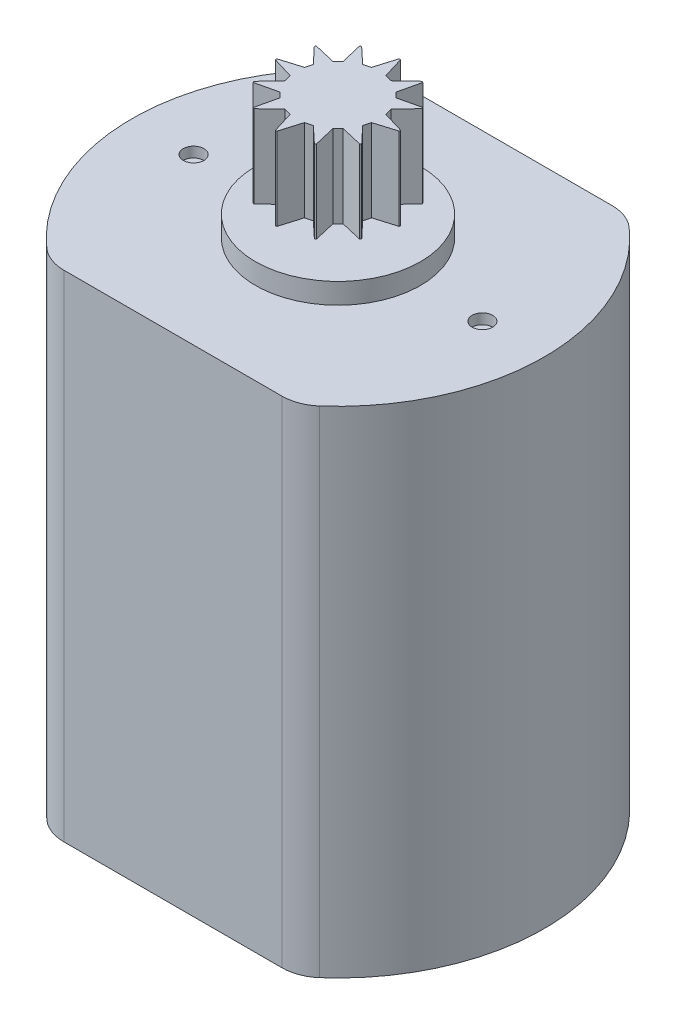
SolidWorks part; units mm, degrees
ref_plane "Front Plane" through (0, 0, 0) normal (0, 0, 1) x (1, 0, 0)
ref_plane "Top Plane" through (0, 0, 0) normal (0, 1, 0) x (1, 0, 0)
ref_plane "Right Plane" through (0, 0, 0) normal (1, 0, 0) x (0, 0, -1)
sketch "Sketch2" plane through (0, 0, 0) normal (0, 1, 0) x (1, 0, 0)
  line L0 (-6.4021, 0) -> (8.186, 0) construction
  line L1 (0, 6.5571) -> (0, -7.7951) construction
  line L2 (-5, 6.9212) -> (-5, -10.6509) construction
  line L3 (-3, 6.9212) -> (-3, -10.7038) construction
  line L4 (3, 7.4505) -> (3, -7.7928) construction
  line L5 (5, 7.4505) -> (5, -8.3221) construction
  line L6 (-10.3041, 4) -> (11.0259, 4) construction
  line L7 (-8.3457, -4) -> (12.6138, -4) construction
  line L8 (-3, 4) -> (3, 4)
  line L11 (3, -4) -> (-3, -4)
  arc A0 (3, 4) -> (3, -4) centre (0, 0) cw
  arc A1 (-3, -4) -> (-3, 4) centre (0, 0) cw
  dimension "D1" = 3
  dimension "D2" = 2
  dimension "D3" = 3
  dimension "D4" = 2
  dimension "D5" = 4
  dimension "D6" = 4
extrude "Boss-Extrude1" add sketch "Sketch2" along normal blind 12
sketch "Sketch3" plane through (0, 0, 0) normal (0, -1, 0) x (-1, 0, 0)
  circle A0 centre (0, 0) radius 2
extrude "Boss-Extrude2" add sketch "Sketch3" along normal blind 1
fillet "Fillet3" radius 1 4 edges at (-3, 6, 4) (3, 6, 4) (-3, 6, -4) (3, 6, -4)
sketch "Sketch4" plane through (0, 12, 0) normal (0, 1, 0) x (1, 0, 0)
  circle A0 centre (0, 0) radius 2
extrude "Boss-Extrude3" add sketch "Sketch4" along normal blind 0.5
sketch "Sketch5" plane through (0, 12, 0) normal (0, 1, 0) x (1, 0, 0)
  circle A0 centre (3.5, 0) radius 0.25
extrude "Cut-Extrude1" cut sketch "Sketch5" against normal blind 0.25
mirror "Mirror1" about plane through (0, 0, 0) normal (1, 0, 0) of "Cut-Extrude1"
sketch "Sketch6" plane through (0, 12.5, 0) normal (0, 1, 0) x (1, 0, 0)
  circle A0 centre (0, 0) radius 0.25
extrude "Boss-Extrude4" add sketch "Sketch6" along normal blind 2.5
sketch "Sketch7" plane through (0, 15, 0) normal (0, 1, 0) x (1, 0, 0)
  circle A0 centre (0, 0) radius 1.5
extrude "Boss-Extrude5" add sketch "Sketch7" against normal blind 2
sketch "Sketch8" plane through (0, 15, 0) normal (0, 1, 0) x (1, 0, 0)
  circle A0 centre (0, 0) radius 1
  circle A1 centre (0, 0) radius 1.5 construction
sketch "Sketch9" plane through (0, 15, 0) normal (0, 1, 0) x (1, 0, 0)
  line L0 (0, 0) -> (0, -4.5648) construction
  line L1 (0, 0) -> (-0.8764, -4.9705) construction
  line L2 (0, 0) -> (-1.8367, -5.0462) construction
  line L3 (-0.342, -0.9397) -> (-0.1736, -0.9848)
  line L4 (-0.1736, -0.9848) -> (0, -1.5561)
  line L5 (0, -1.5561) -> (-0.7815, -1.3537)
  line L6 (0, 0) -> (-3.0573, -5.2955) construction
  line L7 (-0.7815, -1.3537) -> (-0.342, -0.9397)
  circle A0 centre (0, 0) radius 1 construction
  dimension "D1" = 10
  dimension "D2" = 10
  dimension "D3" = 10
extrude "Cut-Extrude11" cut sketch "Sketch9" against normal blind 2
sketch "Sketch10" plane through (0, 0, 0) normal (0, 0, 1) x (1, 0, 0)
  line L0 (0, 0) -> (0, 20.2749) construction
pattern_circular "CirPattern2" count 12 over 360 about axis through (0, 0, 0) along (0, 1, 0) of "Cut-Extrude11"
